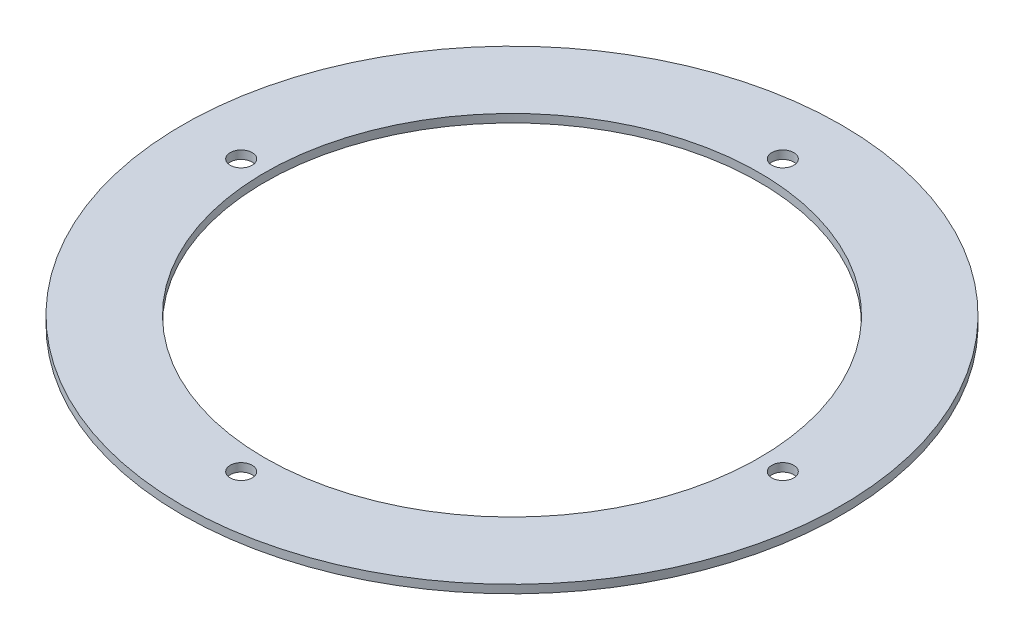
SolidWorks part; units mm, degrees
ref_plane "Front Plane" through (0, 0, 0) normal (0, 0, 1) x (1, 0, 0)
ref_plane "Top Plane" through (0, 0, 0) normal (0, 1, 0) x (1, 0, 0)
ref_plane "Right Plane" through (0, 0, 0) normal (1, 0, 0) x (0, 0, -1)
sketch "Sketch1" plane through (0, 0, 0) normal (0, 1, 0) x (1, 0, 0)
  line L0 (0, 60) -> (0, -60) construction
  line L1 (-60, 0) -> (60, 0) construction
  circle A0 centre (0, 0) radius 60
  circle A1 centre (0, 0) radius 45
  circle A2 centre (0, 0) radius 49.3 construction
  circle A3 centre (0, 49.3) radius 2
  circle A4 centre (49.3, 0) radius 2
  circle A5 centre (0, -49.3) radius 2
  circle A6 centre (-49.3, 0) radius 2
extrude "Boss-Extrude1" add sketch "Sketch1" along normal blind 1.5
